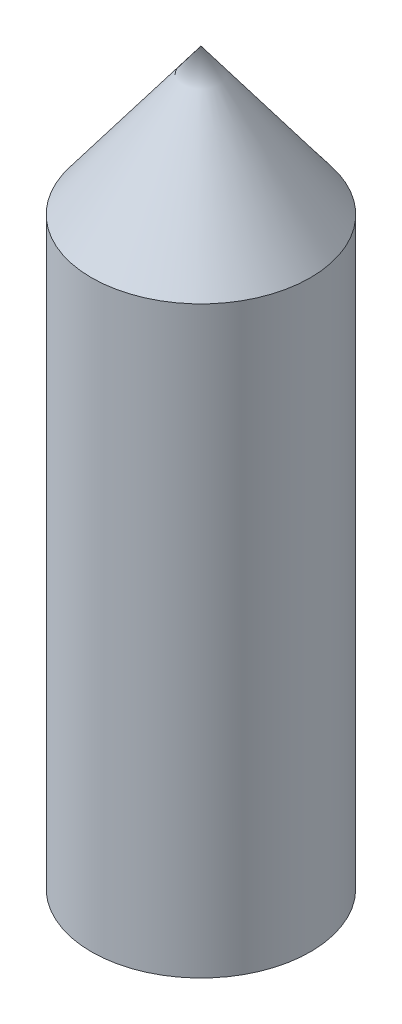
SolidWorks part; units mm, degrees
ref_plane "Plan de face" through (0, 0, 0) normal (0, 0, 1) x (1, 0, 0)
ref_plane "Plan de dessus" through (0, 0, 0) normal (0, 1, 0) x (1, 0, 0)
ref_plane "Plan de droite" through (0, 0, 0) normal (1, 0, 0) x (0, 0, -1)
sketch "Esquisse2" plane through (0, 0, 0) normal (1, 0, 0) x (0, 0, -1)
  line L0 (0, 0) -> (-7.5, 0)
  line L1 (-7.5, 0) -> (-7.5, 40)
  line L2 (-7.5, 40) -> (0, 50)
  line L3 (0, 50) -> (0, 0)
  dimension "D1" = 7.5
  dimension "D2" = 40
  dimension "D3" = 50
revolve "Révolution1" add sketch "Esquisse2" angle 360 about L3
